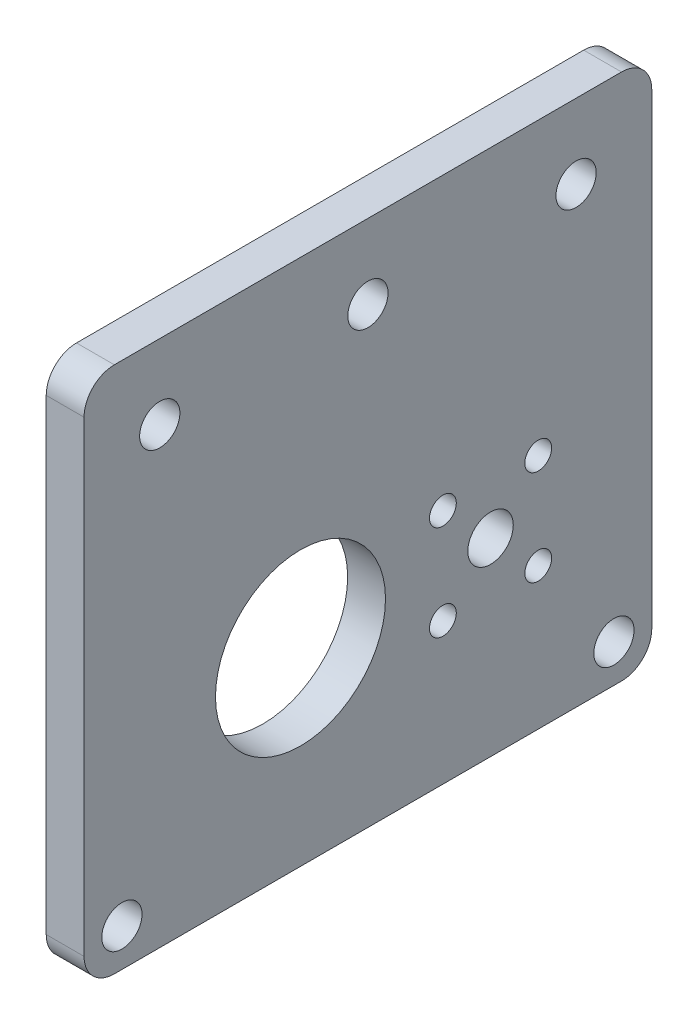
SolidWorks part; units mm, degrees
material "ABS"
ref_plane "Front Plane" through (0, 0, 0) normal (0, 0, 1) x (1, 0, 0)
ref_plane "Top Plane" through (0, 0, 0) normal (0, 1, 0) x (1, 0, 0)
ref_plane "Right Plane" through (0, 0, 0) normal (1, 0, 0) x (0, 0, -1)
sketch "Sketch1" plane through (0, 0, 0) normal (1, 0, 0) x (0, 0, -1)
  line L0 (-68.2, 0) -> (27.05, 0) construction
  line L1 (-8, -8) -> (8, -8) construction
  line L2 (-8, -8) -> (-8, 8) construction
  line L3 (-8, 8) -> (8, 8) construction
  line L4 (8, -8) -> (8, 8) construction
  line L5 (-8, -8) -> (8, 8) construction
  line L6 (-8, 8) -> (8, -8) construction
  line L7 (-68.2, 31.75) -> (27.05, 31.75) construction
  line L8 (-68.2, 31.75) -> (-68.2, -31.75)
  line L9 (-68.2, -31.75) -> (27.05, -31.75)
  line L11 (-68.2, 44.25) -> (27.05, 44.25) construction
  line L13 (27.05, 31.75) -> (27.05, -31.75)
  line L19 (-68.2, 56.75) -> (27.05, 56.75)
  line L20 (-68.2, 56.75) -> (-68.2, 31.75)
  line L21 (-68.2, 31.75) -> (27.05, 31.75) construction
  line L22 (27.05, 56.75) -> (27.05, 31.75)
  circle A0 centre (0, 0) radius 18 construction
  circle A3 centre (0, 0) radius 8 construction
  circle A4 centre (-31.8887, 0) radius 23.8125 construction
  circle A5 centre (0, 0) radius 3.81
  circle A6 centre (-31.8887, 0) radius 14.2621
  circle A11 centre (-31.8887, 0) radius 24.5999 construction
  point P15 (-55.5, 44.25)
  point P16 (-20.575, 44.25)
  point P22 (14.35, 44.25)
  point P32 (-20.575, 44.25)
  dimension "D1" = 36
  dimension "D3" = 16
  dimension "D4" = 47.625
  dimension "D5" = 0.0762
  dimension "D6" = 7.62
  dimension "D7" = 28.5242
  dimension "D15" = 49.1998
  dimension "D2" = 16
  dimension "D8" = 25
  dimension "D9" = 63.5
  dimension "D10" = 12.7
  dimension "D11" = 12.7
  dimension "D12" = 95.25
  dimension "0.75" = 19.05
extrude "Boss-Extrude1" add sketch "Sketch1" along normal blind 6.35
hole_wizard "CSK for M4 Flat Head Machine Screw1" [suppressed] positions "Sketch6" profile "Sketch7" countersink size "M4" standard "ANSI Metric"
sketch "Sketch6" plane through (6.35, 0, 0) normal (1, 0, 0) x (0, 0, -1)
  point P0 (-8, 8)
  point P3 (-8, -8)
  point P6 (8, -8)
  point P9 (8, 8)
sketch "Sketch7" plane through (6.35, 8, 8) normal (0, 1, 0) x (0, 0, -1)
  line L0 (0, 0) -> (0, 6.35)
  line L1 (0, 6.35) -> (2.25, 6.35)
  line L2 (2.25, 6.35) -> (2.25, 2.45)
  line L3 (2.25, 2.45) -> (4.7, 0)
  line L5 (4.7, 0) -> (0, 0)
  line L6 (-2.25, 2.45) -> (-4.7, 0) construction
  line L11 (0, -6.35) -> (0, 107.95) construction
  dimension "Thru Hole Dia." = 4.5
  dimension "Thru Hole Depth" = 6.35
  dimension "Near C'Sink Dia." = 9.4
  dimension "Near C'Sink Angle" = 90
hole_wizard "1/4 Clearance Hole2" positions "Sketch9" profile "Sketch10" hole size "1/4" standard "ANSI Inch" end condition through all
sketch "Sketch9" plane through (6.35, 0, 0) normal (1, 0, 0) x (0, 0, -1)
  line L0 (-68.2, 44.25) -> (27.05, 44.25) construction
  line L1 (27.05, 56.75) -> (27.05, -31.75) construction
  line L2 (-68.2, -31.75) -> (27.05, -31.75) construction
  line L3 (-68.2, 56.75) -> (-68.2, -31.75) construction
  circle A0 centre (-61.85, -25.4) radius 6.35 construction
  circle A1 centre (20.7, -25.4) radius 6.35 construction
  point P0 (-55.5, 44.25)
  point P3 (-20.575, 44.25)
  point P7 (14.35, 44.25)
  point P23 (-61.85, -25.4)
  point P26 (20.7, -25.4)
  dimension "D1" = 12.7
sketch "Sketch10" plane through (6.35, 44.25, 55.5) normal (0, 1, 0) x (0, 0, -1)
  line L0 (0, 0) -> (0, 6.35)
  line L1 (0, 6.35) -> (3.3782, 6.35)
  line L2 (3.3782, 6.35) -> (3.3782, 0)
  line L5 (3.3782, 0) -> (0, 0)
  line L11 (0, -6.35) -> (0, 107.95) construction
  dimension "Thru Hole Dia." = 6.7564
  dimension "Thru Hole Depth" = 6.35
fillet "Fillet1" radius 5.08 4 edges at (3.175, -31.75, -27.05) (3.175, -31.75, 68.2) (3.175, 56.75, -27.05) (3.175, 56.75, 68.2)
hole_wizard "CSK for M4 Flat Head Machine Screw2" positions "Sketch12" profile "Sketch13" countersink size "M4" standard "ANSI Metric" end condition through all
sketch "Sketch12" plane through (0, 0, 0) normal (-1, 0, 0) x (0, 0, 1)
  point P0 (-8, 8)
  point P3 (8, 8)
  point P6 (8, -8)
  point P9 (-8, -8)
sketch "Sketch13" plane through (0, 8, -8) normal (0, 1, 0) x (0, 0, 1)
  line L0 (0, 0) -> (0, 6.35)
  line L1 (0, 6.35) -> (2.25, 6.35)
  line L2 (2.25, 6.35) -> (2.25, 2.45)
  line L3 (2.25, 2.45) -> (4.7, 0)
  line L5 (4.7, 0) -> (0, 0)
  line L6 (-2.25, 2.45) -> (-4.7, 0) construction
  line L11 (0, -6.35) -> (0, 107.95) construction
  dimension "Thru Hole Dia." = 4.5
  dimension "Thru Hole Depth" = 6.35
  dimension "Near C'Sink Dia." = 9.4
  dimension "Near C'Sink Angle" = 90
